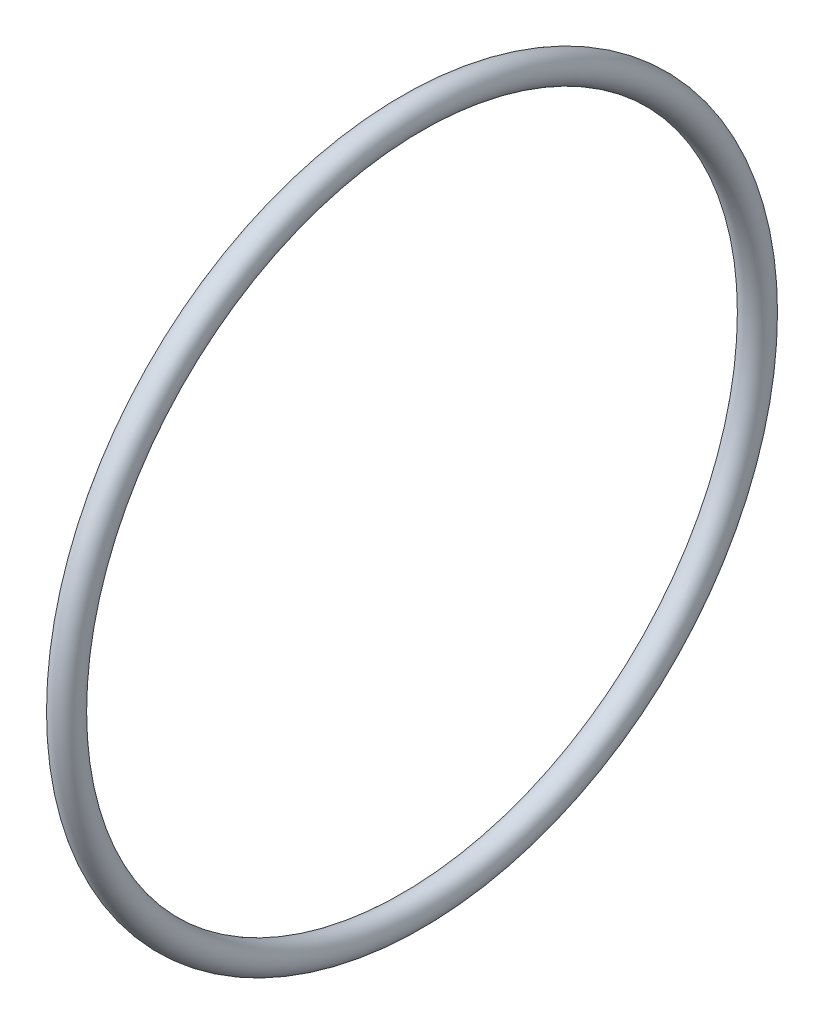
SolidWorks part; units mm, degrees
ref_plane "前视基准面" through (0, 0, 0) normal (0, 0, 1) x (1, 0, 0)
ref_plane "上视基准面" through (0, 0, 0) normal (0, 1, 0) x (1, 0, 0)
ref_plane "右视基准面" through (0, 0, 0) normal (1, 0, 0) x (0, 0, -1)
sketch "草图1" plane through (0, 0, 0) normal (0, 0, 1) x (1, 0, 0)
  line L0 (0, 0) -> (0, 36.5)
  line L2 (-30.5589, 0) -> (29.3664, 0)
  circle A0 centre (0, 36.5) radius 1.5
revolve "旋转2" add sketch "草图1" angle 360 about L2
